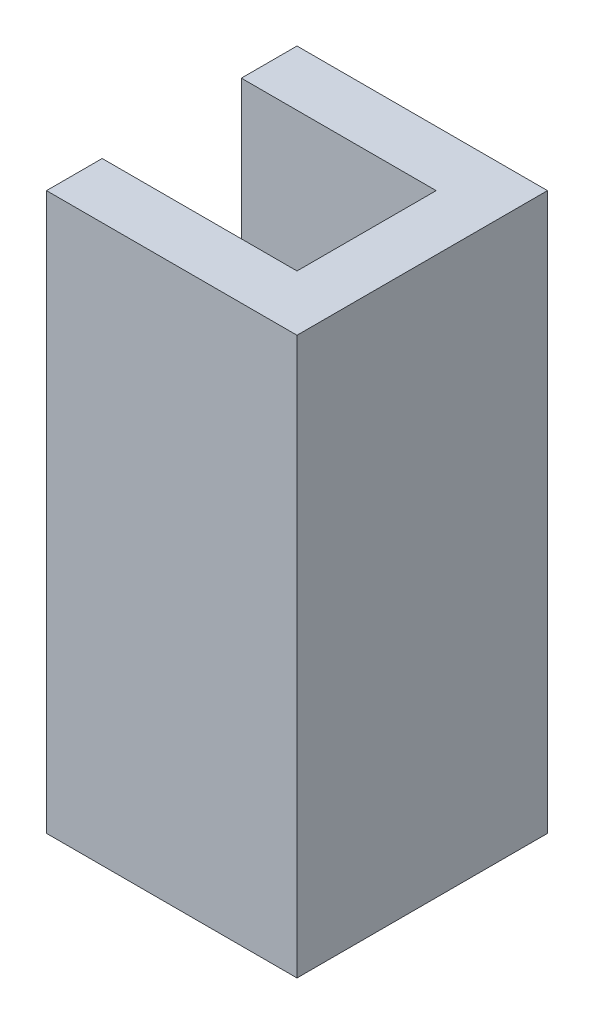
SolidWorks part; units mm, degrees
ref_plane "Front Plane" through (0, 0, 0) normal (0, 0, 1) x (1, 0, 0)
ref_plane "Top Plane" through (0, 0, 0) normal (0, 1, 0) x (1, 0, 0)
ref_plane "Right Plane" through (0, 0, 0) normal (1, 0, 0) x (0, 0, -1)
sketch "Sketch1" plane through (0, 0, 0) normal (0, 1, 0) x (1, 0, 0)
  line L1 (-4.5, -4.5) -> (4.5, -4.5)
  line L2 (-4.5, -4.5) -> (-4.5, 4.5)
  line L3 (-4.5, 4.5) -> (4.5, 4.5)
  line L4 (4.5, -4.5) -> (4.5, 4.5)
  line L5 (-4.5, -4.5) -> (4.5, 4.5) construction
  line L6 (-4.5, 4.5) -> (4.5, -4.5) construction
  line L7 (-2.5, -2.5) -> (2.5, -2.5)
  line L8 (-2.5, -2.5) -> (-2.5, 2.5)
  line L9 (-2.5, 2.5) -> (2.5, 2.5)
  line L10 (2.5, -2.5) -> (2.5, 2.5)
  line L11 (-2.5, -2.5) -> (2.5, 2.5) construction
  line L12 (-2.5, 2.5) -> (2.5, -2.5) construction
  circle A0 centre (0, 0) radius 7 construction
  dimension "D1" = 14
  dimension "D2" = 9
  dimension "D3" = 9
  dimension "D4" = 5
  dimension "D5" = 5
extrude "Boss-Extrude1" add sketch "Sketch1" along normal blind 20
sketch "Sketch2" plane through (0, 20, 0) normal (0, 1, 0) x (1, 0, 0)
  line L0 (-2.5, 2.5) -> (-4.5, 2.5)
  line L1 (-4.5, 4.5) -> (-4.5, -4.5) construction
  line L2 (-2.5, -2.5) -> (-4.5, -2.5)
  line L3 (-4.5, 2.5) -> (-4.5, -2.5)
  line L4 (-2.5, 2.5) -> (-2.5, -2.5)
extrude "Cut-Extrude1" cut sketch "Sketch2" against normal through all
